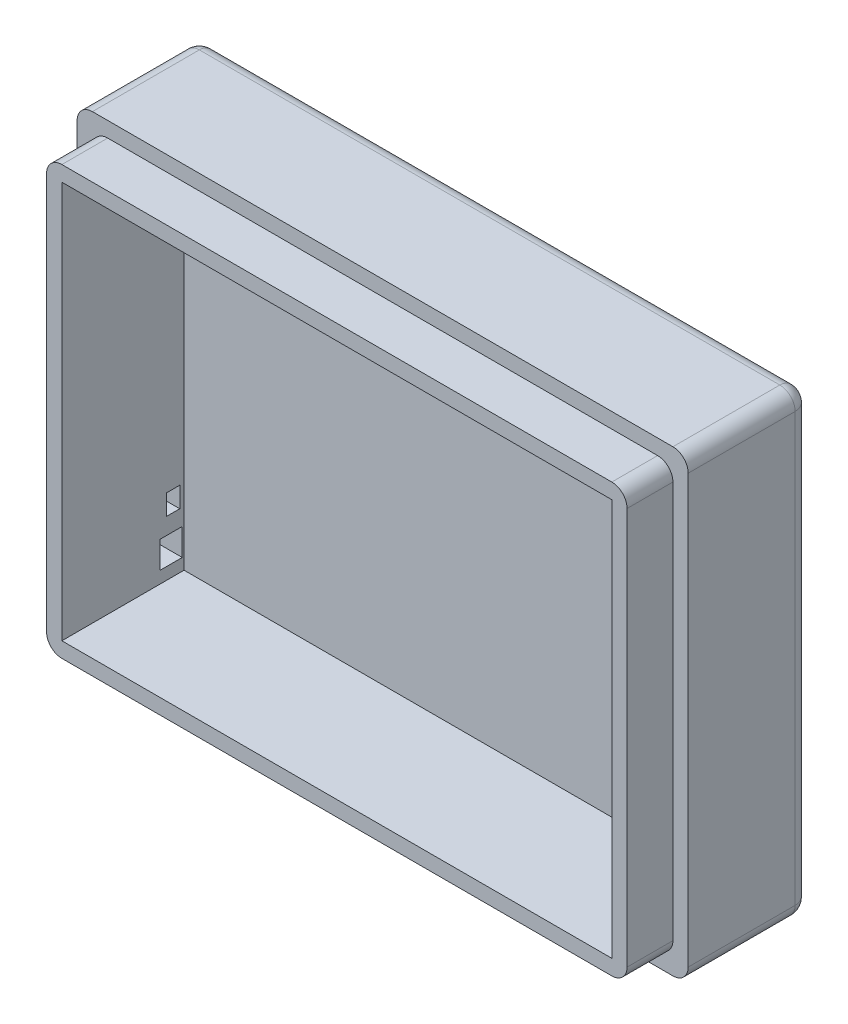
SolidWorks part; units mm, degrees
ref_plane "Front Plane" through (0, 0, 0) normal (0, 0, 1) x (1, 0, 0)
ref_plane "Top Plane" through (0, 0, 0) normal (0, 1, 0) x (1, 0, 0)
ref_plane "Right Plane" through (0, 0, 0) normal (1, 0, 0) x (0, 0, -1)
sketch "Sketch1" plane through (0, 0, 0) normal (0, 0, 1) x (1, 0, 0)
  line L1 (-126.5193, 70.442) -> (73.4807, 70.442)
  line L2 (-126.5193, 70.442) -> (-126.5193, -79.558)
  line L3 (-126.5193, -79.558) -> (73.4807, -79.558)
  line L4 (73.4807, 70.442) -> (73.4807, -79.558)
  dimension "D1" = 200
  dimension "D2" = 150
extrude "Boss-Extrude1" add sketch "Sketch1" along normal blind 40
sketch "Sketch2" plane through (0, 0, 0) normal (0, 0, 1) x (1, 0, 0)
  line L1 (-25.0107, -25.0456) -> (46.9744, -25.0456)
  line L2 (-25.0107, -25.0456) -> (-25.0107, -43.3651)
  line L3 (-25.0107, -43.3651) -> (46.9744, -43.3651)
  line L4 (46.9744, -25.0456) -> (46.9744, -43.3651)
  circle A0 centre (-41.606, -30.9597) radius 6.0845
  circle A1 centre (-57.7703, -30.9597) radius 2.8
  circle A2 centre (-69.4086, -30.9597) radius 2.8
  point P9 (0, 0)
extrude "Cut-Extrude1" cut sketch "Sketch2" along normal blind 7
sketch "Sketch4" plane through (0, 0, 40) normal (0, 0, 1) x (1, 0, 0)
  line L0 (73.4807, -79.558) -> (73.4807, 70.442) construction
  line L1 (73.4807, 70.442) -> (-126.5193, 70.442) construction
  line L2 (-126.5193, 70.442) -> (-126.5193, -79.558) construction
  line L3 (68.4807, -74.558) -> (-121.5193, -74.558)
  line L4 (68.4807, -74.558) -> (68.4807, 65.442)
  line L5 (68.4807, 65.442) -> (-121.5193, 65.442)
  line L6 (-121.5193, -74.558) -> (-121.5193, 65.442)
  line L7 (-126.5193, -79.558) -> (73.4807, -79.558) construction
  dimension "D1" = 5
  dimension "D2" = 5
  dimension "D3" = 5
  dimension "D4" = 5
extrude "Cut-Extrude2" cut sketch "Sketch4" against normal blind 25
sketch "Sketch5" plane through (0, 0, 15) normal (0, 0, 1) x (1, 0, 0)
  line L0 (-121.5193, -74.558) -> (68.4807, -74.558) construction
  line L1 (-121.5193, 65.442) -> (68.4807, 65.442)
  line L2 (-121.5193, 65.442) -> (-121.5193, -74.558)
  line L3 (-121.5193, -74.558) -> (68.4807, -74.558)
  line L4 (68.4807, 65.442) -> (68.4807, -74.558)
  line L5 (68.4807, -74.558) -> (68.4807, 65.442) construction
  dimension "D1" = 190
  dimension "D2" = 140
extrude "Boss-Extrude2" add sketch "Sketch5" along normal blind 40
sketch "Sketch6" plane through (0, 0, 55) normal (0, 0, 1) x (1, 0, 0)
  line L0 (68.4807, 65.442) -> (-121.5193, 65.442) construction
  line L1 (-116.5193, 60.442) -> (63.4807, 60.442)
  line L2 (-116.5193, 60.442) -> (-116.5193, -69.558)
  line L3 (-116.5193, -69.558) -> (63.4807, -69.558)
  line L4 (63.4807, 60.442) -> (63.4807, -69.558)
  line L5 (-121.5193, 65.442) -> (-121.5193, -74.558) construction
  line L6 (68.4807, -74.558) -> (68.4807, 65.442) construction
  line L7 (-121.5193, -74.558) -> (68.4807, -74.558) construction
  dimension "D1" = 5
  dimension "D2" = 5
  dimension "D3" = 5
  dimension "D4" = 5
extrude "Cut-Extrude3" cut sketch "Sketch6" against normal blind 40
fillet "Fillet1" radius 5 12 edges at (68.4807, 65.442, 47.5) (73.4807, 70.442, 20) (-121.5193, 65.442, 47.5) (-126.5193, 70.442, 20) (73.4807, -79.558, 20) (68.4807, -74.558, 47.5) (-121.5193, -74.558, 47.5) (-126.5193, -79.558, 20) (-26.5193, -79.558, 0) (73.4807, -4.558, 0) (-126.5193, -4.558, 0) (-26.5193, 70.442, 0)
fillet "Fillet2" radius 1.5 6 edges at (-66.6086, -30.9597, 0) (-54.9703, -30.9597, 0) (-35.5215, -30.9597, 0) (10.9819, -43.3651, 0) (10.9819, -25.0456, 0) (46.9744, -34.2054, 0)
sketch "Sketch7" plane through (0, 0, 0) normal (0, 0, -1) x (-1, 0, 0)
  circle A0 centre (41.606, -30.9597) radius 6.0845
extrude "Boss-Extrude3" add sketch "Sketch7" against normal blind 7
fillet "Fillet3" radius 1.5 1 edges at (-25.0107, -34.2054, 0)
sketch "Sketch9" plane through (0, 0, 0) normal (0, 0, -1) x (-1, 0, 0)
  line L0 (35.5215, -30.9597) -> (47.7564, -30.9597) construction
  circle A0 centre (41.606, -30.9597) radius 6.0845 construction
  circle A1 centre (41.606, -30.9597) radius 6.0845 construction
  circle A2 centre (41.639, -30.9597) radius 0.7913
extrude "Cut-Extrude4" cut sketch "Sketch9" against normal blind 3
fillet "Fillet4" radius 0.5 1 edges at (-47.6905, -30.9597, 0)
sketch "Sketch10" plane through (0, 0, 7) normal (0, 0, -1) x (-1, 0, 0)
  line L0 (54.9703, -30.9597) -> (60.5703, -30.9597) construction
  line L1 (66.6086, -30.9597) -> (72.2086, -30.9597) construction
  circle A0 centre (57.7703, -30.9597) radius 2.8 construction
  circle A1 centre (57.7703, -30.9597) radius 2.8 construction
  circle A2 centre (57.7703, -30.9597) radius 2.5
  circle A3 centre (69.4086, -30.9597) radius 2.8 construction
  circle A4 centre (69.4086, -30.9597) radius 2.5
extrude "Boss-Extrude4" add sketch "Sketch10" along normal blind 8.5 contours A4 | A2
fillet "Fillet5" radius 1.5 2 edges at (-71.9086, -30.9597, -1.5) (-60.2703, -30.9597, -1.5)
sketch "Sketch13" plane through (0, 0, 7) normal (0, 0, -1) x (-1, 0, 0)
  line L0 (-46.9744, -25.0456) -> (25.0107, -25.0456) construction
  line L1 (-46.4744, -25.5456) -> (24.5107, -25.5456)
  line L2 (-46.4744, -25.5456) -> (-46.4744, -42.8651)
  line L3 (-46.4744, -42.8651) -> (24.5107, -42.8651)
  line L4 (24.5107, -25.5456) -> (24.5107, -42.8651)
  line L5 (-46.9744, -43.3651) -> (-46.9744, -25.0456) construction
  line L6 (25.0107, -43.3651) -> (-46.9744, -43.3651) construction
  line L7 (25.0107, -25.0456) -> (25.0107, -43.3651) construction
  dimension "D1" = 0.5
  dimension "D2" = 0.5
  dimension "D3" = 0.5
  dimension "D4" = 0.5
extrude "Boss-Extrude5" add sketch "Sketch13" along normal blind 6.5
fillet "Fillet6" radius 1.5 4 edges at (-24.5107, -34.2054, 0.5) (10.9819, -42.8651, 0.5) (46.4744, -34.2054, 0.5) (10.9819, -25.5456, 0.5)
sketch "Sketch14" plane through (0, 0, 0.5) normal (0, 0, -1) x (-1, 0, 0)
  line L0 (-44.9744, -27.0456) -> (-44.9744, -41.3651) construction
  line L1 (-43.9744, -28.0456) -> (22.0107, -28.0456)
  line L2 (-43.9744, -28.0456) -> (-43.9744, -40.3651)
  line L3 (-43.9744, -40.3651) -> (22.0107, -40.3651)
  line L4 (22.0107, -28.0456) -> (22.0107, -40.3651)
  line L5 (23.0107, -27.0456) -> (-44.9744, -27.0456) construction
  line L6 (-44.9744, -41.3651) -> (23.0107, -41.3651) construction
  line L7 (23.0107, -41.3651) -> (23.0107, -27.0456) construction
  dimension "D1" = 1
  dimension "D2" = 1
  dimension "D3" = 1
  dimension "D4" = 1
extrude "Cut-Extrude5" cut sketch "Sketch14" against normal blind 0.4
fillet "Fillet7" radius 0.1 4 edges at (-22.0107, -34.2054, 0.5) (10.9819, -40.3651, 0.5) (10.9819, -28.0456, 0.5) (43.9744, -34.2054, 0.5)
sketch "Sketch15" plane through (-126.5193, 0, 0) normal (-1, 0, 0) x (0, 0, 1)
  line L1 (15.6014, -65.6427) -> (22.8099, -65.6427)
  line L2 (15.6014, -65.6427) -> (15.6014, -56.8553)
  line L3 (15.6014, -56.8553) -> (22.8099, -56.8553)
  line L4 (22.8099, -65.6427) -> (22.8099, -56.8553)
  line L5 (16.4146, -51.4268) -> (20.7657, -51.4268)
  line L6 (16.4146, -51.4268) -> (16.4146, -44.7534)
  line L7 (16.4146, -44.7534) -> (20.7657, -44.7534)
  line L8 (20.7657, -51.4268) -> (20.7657, -44.7534)
extrude "Cut-Extrude6" cut sketch "Sketch15" against normal blind 50
